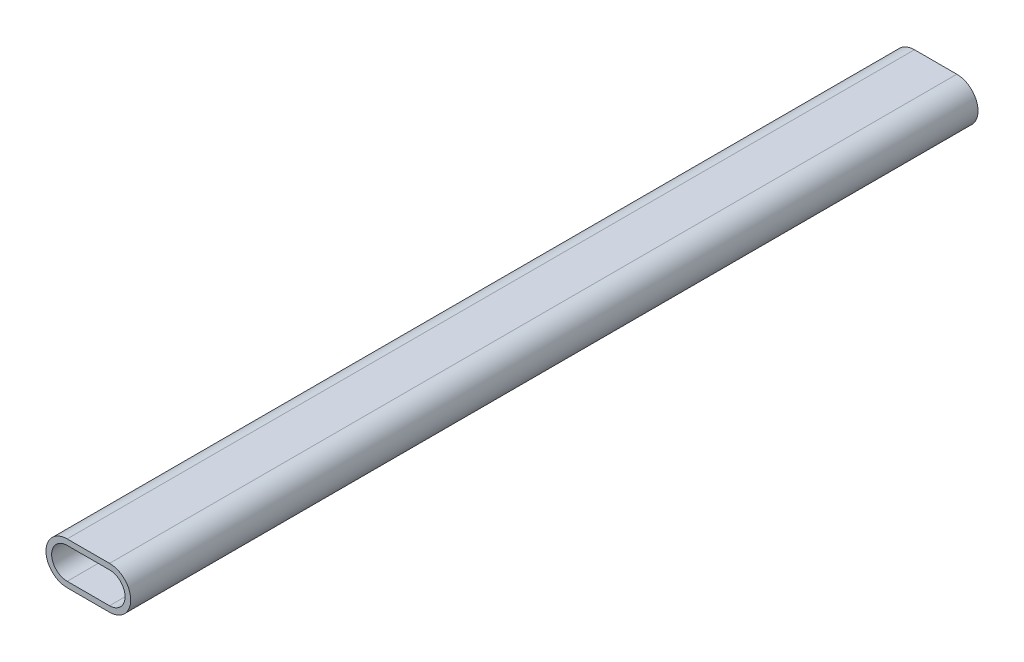
SolidWorks part; units mm, degrees
material "Простая углеродистая сталь"
ref_plane "Спереди" through (0, 0, 0) normal (0, 0, 1) x (1, 0, 0)
ref_plane "Сверху" through (0, 0, 0) normal (0, 1, 0) x (1, 0, 0)
ref_plane "Справа" through (0, 0, 0) normal (1, 0, 0) x (0, 0, -1)
sketch "Эскиз1" plane through (0, 0, 0) normal (0, 0, 1) x (1, 0, 0)
  line L0 (-7.5, 0) -> (7.5, 0) construction
  line L1 (-7.5, 7.5) -> (7.5, 7.5)
  line L2 (-7.5, -7.5) -> (7.5, -7.5)
  line L3 (-7.5, 5.5) -> (7.5, 5.5)
  line L4 (-7.5, -5.5) -> (7.5, -5.5)
  arc A0 (-7.5, 7.5) -> (-7.5, -7.5) centre (-7.5, 0) ccw
  arc A1 (7.5, -7.5) -> (7.5, 7.5) centre (7.5, 0) ccw
  arc A2 (7.5, -5.5) -> (7.5, 5.5) centre (7.5, 0) ccw
  arc A3 (-7.5, 5.5) -> (-7.5, -5.5) centre (-7.5, 0) ccw
  point P2 (0, 0)
  dimension "D1" = 15
  dimension "D2" = 30
  dimension "D3" = 2
extrude "Бобышка-Вытянуть1" add sketch "Эскиз1" along normal blind 300
